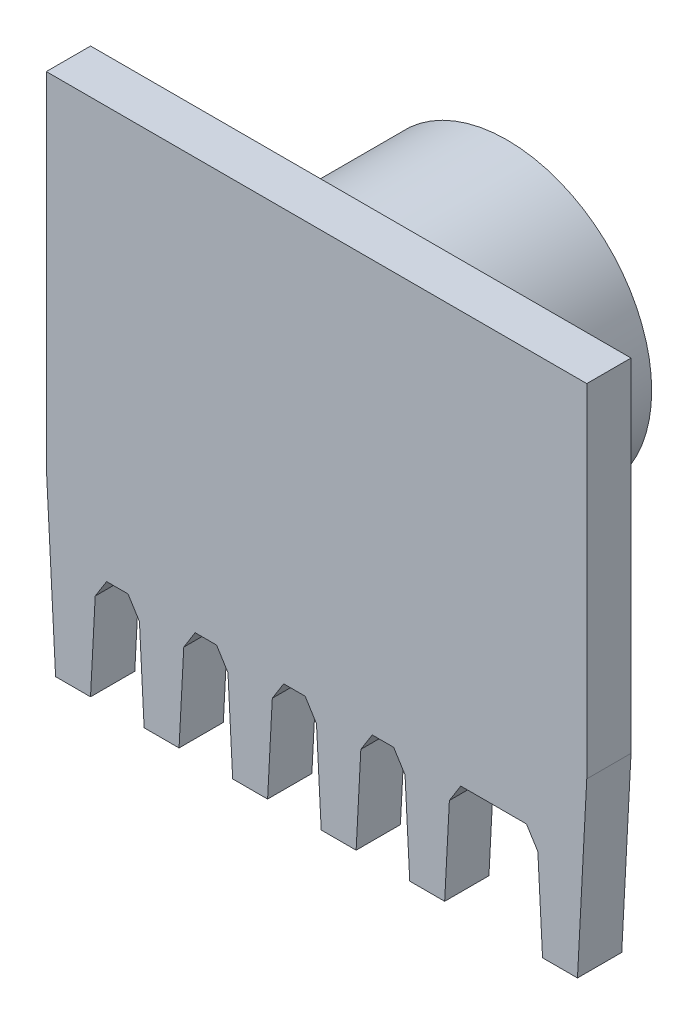
SolidWorks part; units mm, degrees
ref_plane "Front Plane" through (0, 0, 0) normal (0, 0, 1) x (1, 0, 0)
ref_plane "Top Plane" through (0, 0, 0) normal (0, 1, 0) x (1, 0, 0)
ref_plane "Right Plane" through (0, 0, 0) normal (1, 0, 0) x (0, 0, -1)
sketch "Sketch1" plane through (0, 0, 0) normal (0, 0, 1) x (1, 0, 0)
  line L0 (0, 0) -> (0, 17.6) construction
  line L1 (0, 17.6) -> (18.3124, 17.6) construction
  line L2 (18.3124, 17.6) -> (18.3124, 0) construction
  line L3 (18.3124, 0) -> (0, 0) construction
  line L4 (0, 3) -> (18.3124, 3) construction
  line L5 (0, 6) -> (18.3124, 6) construction
  line L6 (0.9062, 6) -> (0.9062, 0) construction
  line L7 (3.9062, 6) -> (3.9062, 0) construction
  line L8 (6.9062, 6) -> (6.9062, 0) construction
  line L9 (9.9062, 6) -> (9.9062, 0) construction
  line L10 (12.9062, 6) -> (12.9062, 0) construction
  line L11 (17.4062, 6) -> (17.4062, 0) construction
  line L12 (0.9062, 3) -> (3.9062, 3) construction
  line L13 (3.9062, 3) -> (6.9062, 3) construction
  line L14 (6.9062, 3) -> (9.9062, 3) construction
  line L15 (9.9062, 3) -> (12.9062, 3) construction
  line L16 (12.9062, 3) -> (17.4062, 3) construction
  line L17 (0.9062, 3) -> (0, 3) construction
  line L18 (17.4062, 3) -> (18.3124, 3) construction
  line L19 (2.4062, 3) -> (2.4062, 0) construction
  line L20 (5.4062, 3) -> (5.4062, 0) construction
  line L21 (8.4062, 3) -> (8.4062, 0) construction
  line L22 (11.4062, 3) -> (11.4062, 0) construction
  line L23 (15.1562, 3) -> (15.1562, 0) construction
  line L24 (14.4062, 3.75) -> (15.9062, 3.75) construction
  line L25 (0, 6) -> (0.3144, 0)
  line L26 (0.3144, 0) -> (1.4979, 0)
  line L27 (1.4979, 0) -> (1.6572, 3.0393)
  line L28 (3.1552, 3.0393) -> (3.3144, 0)
  line L29 (3.3144, 0) -> (4.4979, 0)
  line L30 (4.4979, 0) -> (4.6572, 3.0393)
  line L31 (6.1552, 3.0393) -> (6.3144, 0)
  line L32 (6.3144, 0) -> (7.4979, 0)
  line L33 (7.4979, 0) -> (7.6572, 3.0393)
  line L34 (9.1552, 3.0393) -> (9.3144, 0)
  line L35 (9.3144, 0) -> (10.4979, 0)
  line L36 (10.4979, 0) -> (10.6572, 3.0393)
  line L37 (12.1552, 3.0393) -> (12.3144, 0)
  line L38 (12.3144, 0) -> (13.4979, 0)
  line L39 (13.4979, 0) -> (13.6572, 3.0393)
  line L40 (16.6552, 3.0393) -> (16.8144, 0)
  line L41 (16.8144, 0) -> (17.9979, 0)
  line L42 (17.9979, 0) -> (18.3124, 6)
  line L44 (1.6572, 3.0393) -> (2.0426, 3.656)
  line L45 (0, 6) -> (0, 17.6)
  line L46 (0, 17.6) -> (18.3124, 17.6)
  line L47 (18.3124, 17.6) -> (18.3124, 6)
  line L48 (9.1562, 17.6) -> (9.1562, 6) construction
  line L49 (2.0426, 3.656) -> (2.7698, 3.656)
  line L50 (2.7698, 3.656) -> (3.1552, 3.0393)
  line L51 (4.6572, 3.0393) -> (5.0426, 3.656)
  line L52 (5.0426, 3.656) -> (5.7698, 3.656)
  line L53 (5.7698, 3.656) -> (6.1552, 3.0393)
  line L54 (7.6572, 3.0393) -> (8.0426, 3.656)
  line L55 (8.0426, 3.656) -> (8.7698, 3.656)
  line L56 (8.7698, 3.656) -> (9.1552, 3.0393)
  line L57 (10.6572, 3.0393) -> (11.0426, 3.656)
  line L58 (11.0426, 3.656) -> (11.7698, 3.656)
  line L59 (11.7698, 3.656) -> (12.1552, 3.0393)
  line L60 (13.6572, 3.0393) -> (14.0426, 3.656)
  line L61 (14.0426, 3.656) -> (16.2698, 3.656)
  line L62 (16.2698, 3.656) -> (16.6552, 3.0393)
  arc A0 (3.1552, 3.0393) -> (1.6572, 3.0393) centre (2.4062, 3) ccw construction
  arc A1 (6.1552, 3.0393) -> (4.6572, 3.0393) centre (5.4062, 3) ccw construction
  arc A2 (9.1552, 3.0393) -> (7.6572, 3.0393) centre (8.4062, 3) ccw construction
  arc A3 (12.1552, 3.0393) -> (10.6572, 3.0393) centre (11.4062, 3) ccw construction
  arc A4 (13.6572, 3.0393) -> (14.4062, 3.75) centre (14.4062, 3) cw construction
  arc A5 (16.6552, 3.0393) -> (15.9062, 3.75) centre (15.9062, 3) ccw construction
  dimension "D7" = 0.75
  dimension "D1" = 3
  dimension "D2" = 6
  dimension "D3" = 11.6
  dimension "D4" = 3
  dimension "D6" = 4.5
  dimension "D8" = 3
  dimension "D9" = 18.3124
  dimension "D10" = 17.6
extrude "Boss-Extrude1" add sketch "Sketch1" along normal blind 1.5
sketch "Sketch3" plane through (0, 0, 0) normal (0, 0, 1) x (1, 0, 0)
  line L0 (-0.4005, 6) -> (18.7129, 6)
  line L1 (18.7129, 3) -> (-0.4005, 3) construction
  line L2 (-0.4005, 0) -> (18.7129, 0) construction
  line L3 (-0.4005, -0.5) -> (18.7129, -0.5) construction
  line L4 (18.7129, -0.5) -> (18.7129, 6) construction
  line L5 (-0.4005, 6) -> (-0.4005, -0.5) construction
  line L6 (18.3124, 0) -> (0, 0) construction
  line L7 (0, 3) -> (18.3124, 3) construction
  line L8 (0, 6) -> (18.3124, 6) construction
  line L9 (0.3407, -0.5) -> (0, 6) construction
  line L10 (18.3124, 6) -> (17.9717, -0.5) construction
  line L11 (17.9979, 0) -> (18.3124, 6) construction
  line L12 (0, 6) -> (0.3144, 0) construction
  line L13 (5.4062, 6) -> (5.4062, -0.5) construction
  line L14 (3.9062, 6) -> (3.9062, -0.5) construction
  line L15 (5.4062, 3) -> (5.4062, 0) construction
  line L16 (3.1572, 3) -> (3.3407, -0.5) construction
  line L17 (2.7567, 3) -> (2.9401, -0.5)
  line L18 (3.1552, 3.0393) -> (3.3144, 0) construction
  line L19 (2.9401, -0.5) -> (4.8723, -0.5)
  line L20 (4.8723, -0.5) -> (5.0557, 3)
  line L21 (2.8484, 1.25) -> (3.2478, 1.2709) construction
  line L22 (5.9401, -0.5) -> (5.7567, 3)
  line L26 (7.8723, -0.5) -> (5.9401, -0.5)
  line L27 (8.0557, 3) -> (7.8723, -0.5)
  line L30 (2.4062, -0.5) -> (2.4062, 6) construction
  line L31 (2.4062, 3) -> (2.4062, 0) construction
  line L32 (8.4062, 6) -> (8.4062, -0.5) construction
  line L34 (11.4062, -0.5) -> (11.4062, 6) construction
  line L35 (15.1562, -0.5) -> (15.1562, 6) construction
  line L36 (8.4062, 3) -> (8.4062, 0) construction
  line L37 (11.4062, 3) -> (11.4062, 0) construction
  line L38 (15.1562, 3) -> (15.1562, 0) construction
  line L39 (10.8723, -0.5) -> (11.0557, 3)
  line L40 (8.9401, -0.5) -> (10.8723, -0.5)
  line L41 (8.7567, 3) -> (8.9401, -0.5)
  line L42 (11.9401, -0.5) -> (11.7567, 3)
  line L43 (13.8723, -0.5) -> (11.9401, -0.5)
  line L44 (14.0557, 3) -> (13.8723, -0.5)
  line L45 (16.4401, -0.5) -> (18.3723, -0.5)
  line L46 (16.2567, 3) -> (16.4401, -0.5)
  line L47 (18.3723, -0.5) -> (18.7129, 6)
  line L48 (1.8723, -0.5) -> (-0.0599, -0.5)
  line L49 (2.0557, 3) -> (1.8723, -0.5)
  line L50 (-0.0599, -0.5) -> (-0.4005, 6)
  line L51 (16.2567, 3) -> (14.0557, 3)
  line L52 (11.7567, 3) -> (11.0557, 3)
  line L53 (8.7567, 3) -> (8.0557, 3)
  line L54 (5.7567, 3) -> (5.0557, 3)
  line L55 (2.7567, 3) -> (2.0557, 3)
  dimension "D1" = 0.5
  dimension "D2" = 0.4
ref_plane "Plane1" through (3.9062, 0, 0) normal (1, 0, 0) x (0, 0, -1)
sketch "Sketch4" plane through (3.9062, 0, 0) normal (1, 0, 0) x (0, 0, -1)
  line L0 (0, 6) -> (0, -0.5) construction
  line L1 (0.6, 6) -> (-2.1, 6) construction
  line L2 (0.6, 6) -> (0.6, -0.5) construction
  line L3 (0.6, -0.5) -> (-2.1, -0.5) construction
  line L4 (-2.1, 6) -> (-2.1, -0.5) construction
  line L5 (-0.75, -0.5) -> (-0.75, 6) construction
  line L6 (-1.5, 6) -> (-1.5, -0.5) construction
  line L7 (0.6, 2.4005) -> (-2.1, 2.4005) construction
  line L8 (0.3, 6) -> (0.3, -0.5) construction
  line L9 (0.6, 2.4005) -> (3.846, 6) construction
  line L10 (2.2302, 6) -> (0.6, 4.1923) construction
  line L11 (0.6, 4.1923) -> (1.7139, 3.1878) construction
  line L12 (1.7139, 3.1878) -> (4.25, 6)
  line L13 (4.25, 6) -> (0.6, 6) construction
  line L14 (0.3, 1) -> (-1.8, 1) construction
  line L15 (-2.1, 0) -> (0.6, 0) construction
  line L16 (1.7139, 3.1878) -> (1.4912, 3.3887)
  line L17 (1.4912, 3.3887) -> (0.6, 2.4005)
  line L18 (-3.2139, 3.1878) -> (-5.75, 6)
  line L19 (-3.2139, 3.1878) -> (-2.9912, 3.3887)
  line L20 (-2.9912, 3.3887) -> (-2.1, 2.4005)
  line L21 (-2.1, 6) -> (-5.75, 6) construction
  line L22 (0.6, 3.0724) -> (3.2401, 6) construction
  arc A0 (0.4965, 2.2224) -> (0.6, -0.5) centre (4.2, 1) ccw
  arc A1 (0.6, 2.4005) -> (0.4965, 2.2224) centre (0.9713, 2.0656) ccw
  arc A2 (-2.1, 2.4005) -> (-1.9965, 2.2224) centre (-2.4713, 2.0656) cw
  arc A3 (-1.9965, 2.2224) -> (-2.1, -0.5) centre (-5.7, 1) cw
  dimension "D6" = 0.5
  dimension "D1" = 0.6
  dimension "D2" = 0.3
  dimension "D3" = 1.5
  dimension "D4" = 1
  dimension "D5" = 0.3
  dimension "D7" = 10
sketch "Sketch5" plane through (0, 0, 0) normal (1, 0, 0) x (0, 0, -1)
  line L0 (2.2302, 6) -> (0.6, 4.1923) construction
  line L1 (0.6, 4.1923) -> (1.7139, 3.1878) construction
  line L2 (1.7139, 3.1878) -> (4.25, 6) construction
  line L3 (2.2302, 6) -> (0.6, 4.1923) construction
  line L4 (0.6, 4.1923) -> (1.7139, 3.1878) construction
  line L5 (1.7139, 3.1878) -> (4.25, 6) construction
ref_plane "Plane2" through (0, 2.6105, -2.3541) normal (0, 0.7426, -0.6697) x (1, 0, 0)
sketch "Sketch6" plane through (0, 2.6105, -2.3541) normal (0, 0.7426, -0.6697) x (1, 0, 0)
  line L1 (3.9062, -2.362) -> (3.9062, -0.862) construction
  line L2 (3.9062, -2.362) -> (3.9062, -5.0612) construction
  line L3 (4.6562, -5.0612) -> (3.1562, -5.0612)
  line L4 (4.6562, -1.612) -> (3.1562, -1.612) construction
  line L5 (3.1562, -1.612) -> (3.1562, -5.0612)
  line L6 (4.6562, -1.612) -> (4.6562, -5.0612)
  line L10 (2.4062, -5.0612) -> (15.1562, -5.0612) construction
  line L11 (15.1562, -5.0612) -> (15.1562, -0.862) construction
  line L12 (15.1562, -0.862) -> (2.4062, -0.862) construction
  line L13 (2.4062, -0.862) -> (2.4062, -5.0612) construction
  line L14 (15.1562, 0.3349) -> (15.1562, -4.0182) construction
  line L15 (2.4062, 0.3349) -> (2.4062, -4.0182) construction
  line L16 (11.4062, -5.0612) -> (11.4062, -0.862) construction
  line L17 (8.4062, -5.0612) -> (8.4062, -0.862) construction
  line L18 (5.4062, -5.0612) -> (5.4062, -0.862) construction
  line L19 (5.4062, -4.0182) -> (5.4062, 0.3349) construction
  line L20 (8.4062, -4.0182) -> (8.4062, 0.3349) construction
  line L21 (11.4062, 0.3349) -> (11.4062, -4.0182) construction
  line L22 (0.1562, -1.612) -> (0.1562, -5.0612)
  line L23 (0.1562, -5.0612) -> (1.6562, -5.0612)
  line L24 (1.6562, -1.612) -> (1.6562, -5.0612)
  line L25 (7.6562, -1.612) -> (7.6562, -5.0612)
  line L26 (6.1562, -5.0612) -> (7.6562, -5.0612)
  line L27 (6.1562, -1.612) -> (6.1562, -5.0612)
  line L28 (10.6562, -1.612) -> (10.6562, -5.0612)
  line L29 (10.6562, -5.0612) -> (9.1562, -5.0612)
  line L30 (9.1562, -1.612) -> (9.1562, -5.0612)
  line L31 (13.6562, -1.612) -> (13.6562, -5.0612)
  line L32 (12.1562, -5.0612) -> (13.6562, -5.0612)
  line L33 (12.1562, -1.612) -> (12.1562, -5.0612)
  line L34 (18.1562, -1.612) -> (18.1562, -5.0612)
  line L35 (18.1562, -5.0612) -> (16.6562, -5.0612)
  line L36 (16.6562, -1.612) -> (16.6562, -5.0612)
  circle A0 centre (3.9062, -1.612) radius 0.75 construction
  arc A1 (4.6562, -1.612) -> (3.1562, -1.612) centre (3.9062, -1.612) ccw
  arc A2 (0.1562, -1.612) -> (1.6562, -1.612) centre (0.9062, -1.612) cw
  arc A3 (6.1562, -1.612) -> (7.6562, -1.612) centre (6.9062, -1.612) cw
  arc A4 (10.6562, -1.612) -> (9.1562, -1.612) centre (9.9062, -1.612) ccw
  arc A5 (12.1562, -1.612) -> (13.6562, -1.612) centre (12.9062, -1.612) cw
  arc A6 (18.1562, -1.612) -> (16.6562, -1.612) centre (17.4062, -1.612) ccw
ref_plane "Plane3" through (0, 1.6223, -1.463) normal (0, 0.7426, -0.6697) x (1, 0, 0)
sketch "Sketch7" plane through (0, 1.6223, -1.463) normal (0, 0.7426, -0.6697) x (1, 0, 0)
  line L0 (3.1562, -1.612) -> (3.1562, -5.0612) construction
  line L1 (4.6562, -5.0612) -> (3.1562, -5.0612) construction
  line L2 (4.6562, -1.612) -> (4.6562, -5.0612) construction
  line L3 (3.1562, -1.612) -> (3.1562, -5.0612) construction
  line L4 (4.6562, -5.0612) -> (3.1562, -5.0612) construction
  line L5 (4.6562, -1.612) -> (4.6562, -5.0612) construction
  line L6 (3.9062, -0.862) -> (3.9062, -5.0612) construction
  line L7 (4.6562, -1.612) -> (3.1562, -1.612) construction
  line L8 (4.6562, -2.362) -> (3.1562, -2.362) construction
  line L9 (3.4562, -1.612) -> (3.4562, -2.362)
  line L10 (3.4562, -2.362) -> (4.3562, -2.362)
  line L11 (4.3562, -2.362) -> (4.3562, -1.612)
  line L12 (2.4062, -0.862) -> (2.4062, -5.0612) construction
  line L13 (2.4062, -5.0612) -> (15.1562, -5.0612) construction
  line L14 (15.1562, -0.862) -> (2.4062, -0.862) construction
  line L15 (5.4062, -5.0612) -> (5.4062, -0.862) construction
  line L16 (8.4062, -5.0612) -> (8.4062, -0.862) construction
  line L17 (11.4062, -5.0612) -> (11.4062, -0.862) construction
  line L18 (15.1562, -5.0612) -> (15.1562, -0.862) construction
  line L19 (2.4062, -0.862) -> (2.4062, -5.0612) construction
  line L20 (2.4062, -5.0612) -> (15.1562, -5.0612) construction
  line L21 (15.1562, -0.862) -> (2.4062, -0.862) construction
  line L22 (5.4062, -5.0612) -> (5.4062, -0.862) construction
  line L23 (8.4062, -5.0612) -> (8.4062, -0.862) construction
  line L24 (11.4062, -5.0612) -> (11.4062, -0.862) construction
  line L25 (15.1562, -5.0612) -> (15.1562, -0.862) construction
  line L26 (0.4562, -2.362) -> (0.4562, -1.612)
  line L27 (1.3562, -2.362) -> (0.4562, -2.362)
  line L28 (1.3562, -1.612) -> (1.3562, -2.362)
  line L29 (7.3562, -2.362) -> (6.4562, -2.362)
  line L30 (7.3562, -1.612) -> (7.3562, -2.362)
  line L31 (6.4562, -2.362) -> (6.4562, -1.612)
  line L32 (9.4562, -1.612) -> (9.4562, -2.362)
  line L33 (10.3562, -2.362) -> (10.3562, -1.612)
  line L34 (9.4562, -2.362) -> (10.3562, -2.362)
  line L35 (13.3562, -1.612) -> (13.3562, -2.362)
  line L36 (12.4562, -2.362) -> (12.4562, -1.612)
  line L37 (13.3562, -2.362) -> (12.4562, -2.362)
  line L38 (16.9562, -1.612) -> (16.9562, -2.362)
  line L39 (17.8562, -2.362) -> (17.8562, -1.612)
  line L40 (16.9562, -2.362) -> (17.8562, -2.362)
  arc A0 (4.6562, -1.612) -> (3.1562, -1.612) centre (3.9062, -1.612) ccw construction
  arc A1 (4.6562, -1.612) -> (3.1562, -1.612) centre (3.9062, -1.612) ccw construction
  circle A2 centre (3.9062, -1.612) radius 0.45 construction
  arc A3 (4.3562, -1.612) -> (3.4562, -1.612) centre (3.9062, -1.612) ccw
  arc A4 (0.4562, -1.612) -> (1.3562, -1.612) centre (0.9062, -1.612) cw
  arc A5 (6.4562, -1.612) -> (7.3562, -1.612) centre (6.9062, -1.612) cw
  arc A6 (10.3562, -1.612) -> (9.4562, -1.612) centre (9.9062, -1.612) ccw
  arc A7 (12.4562, -1.612) -> (13.3562, -1.612) centre (12.9062, -1.612) cw
  arc A8 (17.8562, -1.612) -> (16.9562, -1.612) centre (17.4062, -1.612) ccw
ref_plane "bisect" through (0, 0, 0.75) normal (0, 0, 1) x (1, 0, 0)
ref_plane "insert_surface" through (0, 6, 0) normal (0, 1, 0) x (1, 0, 0)
sketch "Sketch8" plane through (0, 6, 0) normal (0, 1, 0) x (1, 0, 0)
  line L0 (18.7129, -0.75) -> (-0.4005, -0.75) construction
  line L1 (-0.4005, 0.6) -> (18.7129, 0.6)
  line L2 (-0.4005, 0.6) -> (-0.4005, -2.1)
  line L3 (-0.4005, -2.1) -> (18.7129, -2.1)
  line L4 (18.7129, 0.6) -> (18.7129, -2.1)
  line L5 (9.1562, 0.6) -> (9.1562, -2.1) construction
  line L6 (0, 0) -> (18.3124, 0) construction
  line L7 (0, 0) -> (0, -1.5) construction
  line L8 (0, -1.5) -> (18.3124, -1.5) construction
  line L9 (18.3124, 0) -> (18.3124, -1.5) construction
  line L10 (18.7129, 0.3) -> (-0.4005, 0.3) construction
  line L11 (18.7129, -1.8) -> (-0.4005, -1.8) construction
sketch "Sketch9" plane through (0, 0, 0) normal (0, 0, 1) x (1, 0, 0)
  line L0 (18.3723, -0.5) -> (18.7129, 6) construction
  line L1 (-0.4005, 6) -> (18.7129, 6) construction
  line L2 (-0.0599, -0.5) -> (-0.4005, 6) construction
  line L3 (1.8723, -0.5) -> (-0.0599, -0.5) construction
  line L4 (2.0557, 3) -> (1.8723, -0.5) construction
  line L5 (2.7567, 3) -> (2.0557, 3) construction
  line L6 (2.7567, 3) -> (2.9401, -0.5) construction
  line L7 (2.9401, -0.5) -> (4.8723, -0.5) construction
  line L8 (4.8723, -0.5) -> (5.0557, 3) construction
  line L9 (5.7567, 3) -> (5.0557, 3) construction
  line L10 (5.9401, -0.5) -> (5.7567, 3) construction
  line L11 (7.8723, -0.5) -> (5.9401, -0.5) construction
  line L12 (8.0557, 3) -> (7.8723, -0.5) construction
  line L13 (8.7567, 3) -> (8.0557, 3) construction
  line L14 (8.7567, 3) -> (8.9401, -0.5) construction
  line L15 (8.9401, -0.5) -> (10.8723, -0.5) construction
  line L16 (10.8723, -0.5) -> (11.0557, 3) construction
  line L17 (11.7567, 3) -> (11.0557, 3) construction
  line L18 (11.9401, -0.5) -> (11.7567, 3) construction
  line L19 (13.8723, -0.5) -> (11.9401, -0.5) construction
  line L20 (14.0557, 3) -> (13.8723, -0.5) construction
  line L21 (16.2567, 3) -> (14.0557, 3) construction
  line L22 (16.2567, 3) -> (16.4401, -0.5) construction
  line L23 (16.4401, -0.5) -> (18.3723, -0.5) construction
  line L24 (18.3723, -0.5) -> (18.7129, 6)
  line L25 (-0.4005, 6) -> (18.7129, 6) construction
  line L26 (-0.0599, -0.5) -> (-0.4005, 6)
  line L27 (1.8723, -0.5) -> (-0.0599, -0.5)
  line L28 (2.0557, 3) -> (1.8723, -0.5)
  line L29 (2.7567, 3) -> (2.0557, 3) construction
  line L30 (2.7567, 3) -> (2.9401, -0.5)
  line L31 (2.9401, -0.5) -> (4.8723, -0.5)
  line L32 (4.8723, -0.5) -> (5.0557, 3)
  line L33 (5.7567, 3) -> (5.0557, 3) construction
  line L34 (5.9401, -0.5) -> (5.7567, 3)
  line L35 (7.8723, -0.5) -> (5.9401, -0.5)
  line L36 (8.0557, 3) -> (7.8723, -0.5)
  line L37 (8.7567, 3) -> (8.0557, 3) construction
  line L38 (8.7567, 3) -> (8.9401, -0.5)
  line L39 (8.9401, -0.5) -> (10.8723, -0.5)
  line L40 (10.8723, -0.5) -> (11.0557, 3)
  line L41 (11.7567, 3) -> (11.0557, 3) construction
  line L42 (11.9401, -0.5) -> (11.7567, 3)
  line L43 (13.8723, -0.5) -> (11.9401, -0.5)
  line L44 (14.0557, 3) -> (13.8723, -0.5)
  line L45 (16.2567, 3) -> (14.0557, 3) construction
  line L46 (16.2567, 3) -> (16.4401, -0.5)
  line L47 (16.4401, -0.5) -> (18.3723, -0.5)
  line L48 (16.2567, 3) -> (16.2567, 6)
  line L49 (14.0557, 3) -> (14.0557, 6)
  line L50 (11.7567, 3) -> (11.7567, 6)
  line L51 (18.7129, 6) -> (-0.4005, 6) construction
  line L52 (11.0557, 3) -> (11.0557, 6)
  line L53 (-0.4005, 6) -> (18.7129, 6) construction
  line L54 (8.7567, 3) -> (8.7567, 6)
  line L55 (8.0557, 3) -> (8.0557, 6)
  line L58 (5.7567, 3) -> (5.7567, 6)
  line L60 (5.0557, 3) -> (5.0557, 6)
  line L62 (15.1562, -0.5) -> (15.1562, 6) construction
  line L63 (15.1562, -0.5) -> (15.1562, 6) construction
  line L64 (2.7567, 3) -> (2.7567, 6)
  line L65 (2.0557, 3) -> (2.0557, 6)
  line L67 (18.7129, 6) -> (16.2567, 6)
  line L68 (14.0557, 6) -> (11.7567, 6)
  line L69 (11.0557, 6) -> (8.7567, 6)
  line L70 (8.0557, 6) -> (5.7567, 6)
  line L71 (5.0557, 6) -> (2.7567, 6)
  line L72 (2.0557, 6) -> (-0.4005, 6)
sketch "rgb_led" plane through (0, 0, 1.5) normal (0, 0, 1) x (1, 0, 0)
  line L0 (18.3124, 14.6) -> (0, 14.6) construction
  line L1 (18.3124, 6) -> (18.3124, 17.6) construction
  line L2 (0, 17.6) -> (0, 6) construction
  line L3 (9.1562, 17.6) -> (9.1562, 14.6) construction
  line L4 (18.3124, 17.6) -> (0, 17.6) construction
  line L6 (12.0562, 16.4) -> (6.2562, 16.4)
  line L7 (12.0562, 16.4) -> (12.0562, 12.8)
  line L8 (12.0562, 12.8) -> (6.2562, 12.8)
  line L9 (6.2562, 16.4) -> (6.2562, 12.8)
  dimension "D1" = 3
  dimension "D2" = 3.6
  dimension "D3" = 5.8
sketch "Sketch10" plane through (0, 0, 0) normal (0, 0, 1) x (1, 0, 0)
  line L0 (0, 6) -> (18.3124, 6) construction
  line L1 (0, 6) -> (0, 17.6) construction
  line L2 (0, 17.6) -> (18.3124, 17.6) construction
  line L3 (9.1124, 12) -> (9.1124, 6) construction
  line L4 (9.1124, 12) -> (18.3124, 12) construction
  line L5 (18.3124, 6) -> (18.3124, 17.6) construction
  circle A0 centre (9.1124, 12) radius 4.9
  dimension "D3" = 9.8
  dimension "D1" = 9.2
  dimension "D2" = 6
extrude "Boss-Extrude2" add sketch "Sketch10" against normal blind 5
ref_plane "right_center" through (9.1562, 0, 0) normal (1, 0, 0) x (0, 0, -1)
